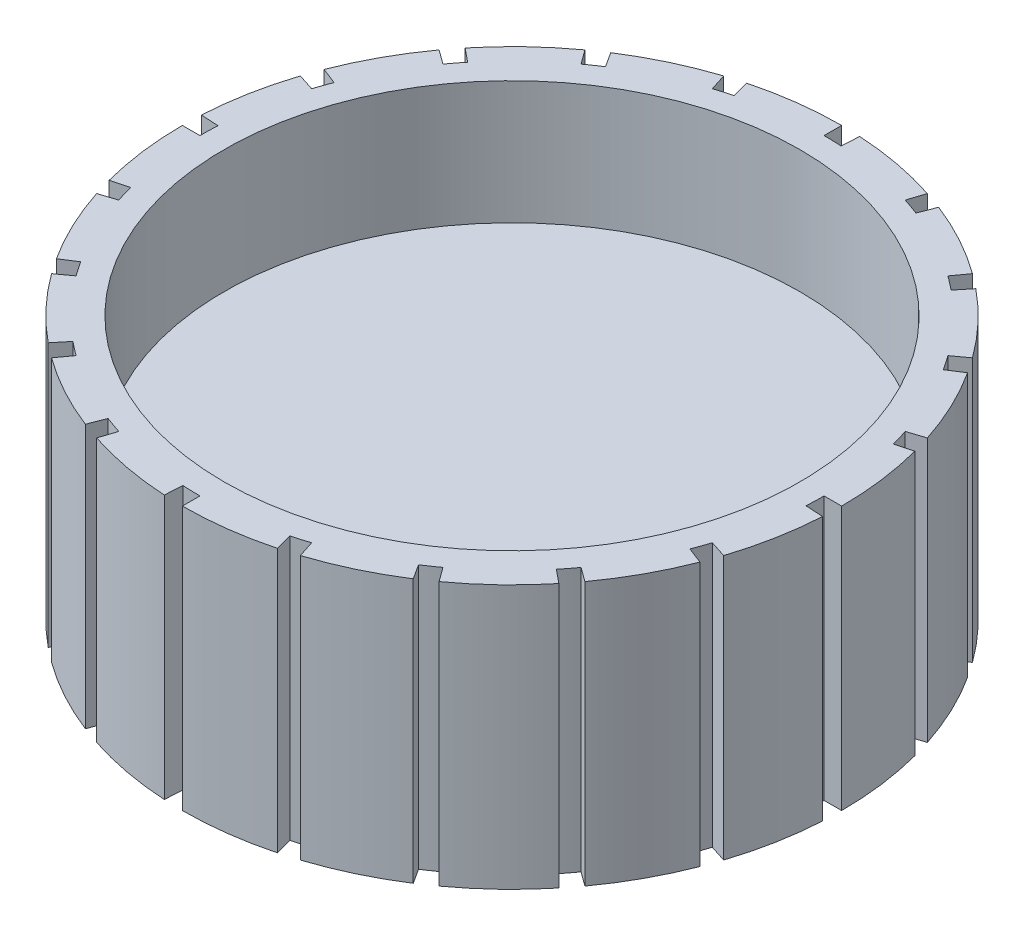
SolidWorks part; units mm, degrees
ref_plane "前视基准面" through (0, 0, 0) normal (0, 0, 1) x (1, 0, 0)
ref_plane "上视基准面" through (0, 0, 0) normal (0, 1, 0) x (1, 0, 0)
ref_plane "右视基准面" through (0, 0, 0) normal (1, 0, 0) x (0, 0, -1)
sketch "草图1" plane through (0, 0, 0) normal (0, 1, 0) x (1, 0, 0)
  circle A0 centre (0, 0) radius 37.5
  dimension "D1" = 75
extrude "凸台-拉伸1" add sketch "草图1" along normal blind 30
sketch "草图2" plane through (0, 30, 0) normal (0, 1, 0) x (1, 0, 0)
  circle A0 centre (0, 0) radius 32.75
  dimension "D1" = 65.5
extrude "切除-拉伸1" cut sketch "草图2" against normal blind 14
sketch "草图3" plane through (0, 30, 0) normal (0, 1, 0) x (1, 0, 0)
  line L4 (0, 0) -> (-49.5597, 0) construction
  line L5 (0, 0) -> (-47.6161, 2.6869) construction
  line L6 (-35.4436, 2) -> (-35.5, 0) construction
  line L7 (-35.4436, 2) -> (-37.4404, 2.1127)
  line L8 (-35.5, 0) -> (-37.5, 0)
  line L9 (-33.7625, 10.9701) -> (-35.6646, 11.5881)
  line L10 (-33.0908, 12.8548) -> (-34.9551, 13.579)
  line L11 (-28.7201, 20.8664) -> (-30.3381, 22.0419)
  line L12 (-27.4989, 22.4513) -> (-29.0482, 23.7161)
  line L13 (-20.8664, 28.7201) -> (-22.0419, 30.3381)
  line L14 (-19.2152, 29.8501) -> (-20.2977, 31.5318)
  line L15 (-10.9701, 33.7625) -> (-11.5881, 35.6646)
  line L16 (-9.0506, 34.3269) -> (-9.5605, 36.2608)
  line L17 (0, 35.5) -> (0, 37.5)
  line L18 (2, 35.4436) -> (2.1127, 37.4404)
  line L19 (10.9701, 33.7625) -> (11.5881, 35.6646)
  line L20 (12.8548, 33.0908) -> (13.579, 34.9551)
  line L21 (20.8664, 28.7201) -> (22.0419, 30.3381)
  line L22 (22.4513, 27.4989) -> (23.7161, 29.0482)
  line L23 (28.7201, 20.8664) -> (30.3381, 22.0419)
  line L24 (29.8501, 19.2152) -> (31.5318, 20.2977)
  line L25 (33.7625, 10.9701) -> (35.6646, 11.5881)
  line L26 (34.3269, 9.0506) -> (36.2608, 9.5605)
  line L27 (35.5, 0) -> (37.5, 0)
  line L28 (35.4436, -2) -> (37.4404, -2.1127)
  line L29 (33.7625, -10.9701) -> (35.6646, -11.5881)
  line L30 (33.0908, -12.8548) -> (34.9551, -13.579)
  line L31 (28.7201, -20.8664) -> (30.3381, -22.0419)
  line L32 (27.4989, -22.4513) -> (29.0482, -23.7161)
  line L33 (20.8664, -28.7201) -> (22.0419, -30.3381)
  line L34 (19.2152, -29.8501) -> (20.2977, -31.5318)
  line L35 (10.9701, -33.7625) -> (11.5881, -35.6646)
  line L36 (9.0506, -34.3269) -> (9.5605, -36.2608)
  line L37 (0, -35.5) -> (0, -37.5)
  line L38 (-2, -35.4436) -> (-2.1127, -37.4404)
  line L39 (-10.9701, -33.7625) -> (-11.5881, -35.6646)
  line L40 (-12.8548, -33.0908) -> (-13.579, -34.9551)
  line L41 (-20.8664, -28.7201) -> (-22.0419, -30.3381)
  line L42 (-22.4513, -27.4989) -> (-23.7161, -29.0482)
  line L43 (-28.7201, -20.8664) -> (-30.3381, -22.0419)
  line L44 (-29.8501, -19.2152) -> (-31.5318, -20.2977)
  line L45 (-33.7625, -10.9701) -> (-35.6646, -11.5881)
  line L46 (-34.3269, -9.0506) -> (-36.2608, -9.5605)
  circle A0 centre (0, 0) radius 37.5 construction
  arc A1 (-35.4436, 2) -> (-35.5, 0) centre (0, 0) ccw
  arc A2 (-37.5, 0) -> (-37.4404, 2.1127) centre (0, 0) cw
  arc A3 (-35.6646, 11.5881) -> (-34.9551, 13.579) centre (0, 0) cw
  arc A4 (-33.0908, 12.8548) -> (-33.7625, 10.9701) centre (0, 0) ccw
  arc A5 (-30.3381, 22.0419) -> (-29.0482, 23.7161) centre (0, 0) cw
  arc A6 (-27.4989, 22.4513) -> (-28.7201, 20.8664) centre (0, 0) ccw
  arc A7 (-22.0419, 30.3381) -> (-20.2977, 31.5318) centre (0, 0) cw
  arc A8 (-19.2152, 29.8501) -> (-20.8664, 28.7201) centre (0, 0) ccw
  arc A9 (-11.5881, 35.6646) -> (-9.5605, 36.2608) centre (0, 0) cw
  arc A10 (-9.0506, 34.3269) -> (-10.9701, 33.7625) centre (0, 0) ccw
  arc A11 (0, 37.5) -> (2.1127, 37.4404) centre (0, 0) cw
  arc A12 (2, 35.4436) -> (0, 35.5) centre (0, 0) ccw
  arc A13 (11.5881, 35.6646) -> (13.579, 34.9551) centre (0, 0) cw
  arc A14 (12.8548, 33.0908) -> (10.9701, 33.7625) centre (0, 0) ccw
  arc A15 (22.0419, 30.3381) -> (23.7161, 29.0482) centre (0, 0) cw
  arc A16 (22.4513, 27.4989) -> (20.8664, 28.7201) centre (0, 0) ccw
  arc A17 (30.3381, 22.0419) -> (31.5318, 20.2977) centre (0, 0) cw
  arc A18 (29.8501, 19.2152) -> (28.7201, 20.8664) centre (0, 0) ccw
  arc A19 (35.6646, 11.5881) -> (36.2608, 9.5605) centre (0, 0) cw
  arc A20 (34.3269, 9.0506) -> (33.7625, 10.9701) centre (0, 0) ccw
  arc A21 (37.5, 0) -> (37.4404, -2.1127) centre (0, 0) cw
  arc A22 (35.4436, -2) -> (35.5, 0) centre (0, 0) ccw
  arc A23 (35.6646, -11.5881) -> (34.9551, -13.579) centre (0, 0) cw
  arc A24 (33.0908, -12.8548) -> (33.7625, -10.9701) centre (0, 0) ccw
  arc A25 (30.3381, -22.0419) -> (29.0482, -23.7161) centre (0, 0) cw
  arc A26 (27.4989, -22.4513) -> (28.7201, -20.8664) centre (0, 0) ccw
  arc A27 (22.0419, -30.3381) -> (20.2977, -31.5318) centre (0, 0) cw
  arc A28 (19.2152, -29.8501) -> (20.8664, -28.7201) centre (0, 0) ccw
  arc A29 (11.5881, -35.6646) -> (9.5605, -36.2608) centre (0, 0) cw
  arc A30 (9.0506, -34.3269) -> (10.9701, -33.7625) centre (0, 0) ccw
  arc A31 (0, -37.5) -> (-2.1127, -37.4404) centre (0, 0) cw
  arc A32 (-2, -35.4436) -> (0, -35.5) centre (0, 0) ccw
  arc A33 (-11.5881, -35.6646) -> (-13.579, -34.9551) centre (0, 0) cw
  arc A34 (-12.8548, -33.0908) -> (-10.9701, -33.7625) centre (0, 0) ccw
  arc A35 (-22.0419, -30.3381) -> (-23.7161, -29.0482) centre (0, 0) cw
  arc A36 (-22.4513, -27.4989) -> (-20.8664, -28.7201) centre (0, 0) ccw
  arc A37 (-30.3381, -22.0419) -> (-31.5318, -20.2977) centre (0, 0) cw
  arc A38 (-29.8501, -19.2152) -> (-28.7201, -20.8664) centre (0, 0) ccw
  arc A39 (-35.6646, -11.5881) -> (-36.2608, -9.5605) centre (0, 0) cw
  arc A40 (-34.3269, -9.0506) -> (-33.7625, -10.9701) centre (0, 0) ccw
  point P88 (0, 0)
  dimension "D1" = 2
  dimension "D2" = 2
  dimension "D3" = 20
extrude "切除-拉伸2" cut sketch "草图3" against normal through all
